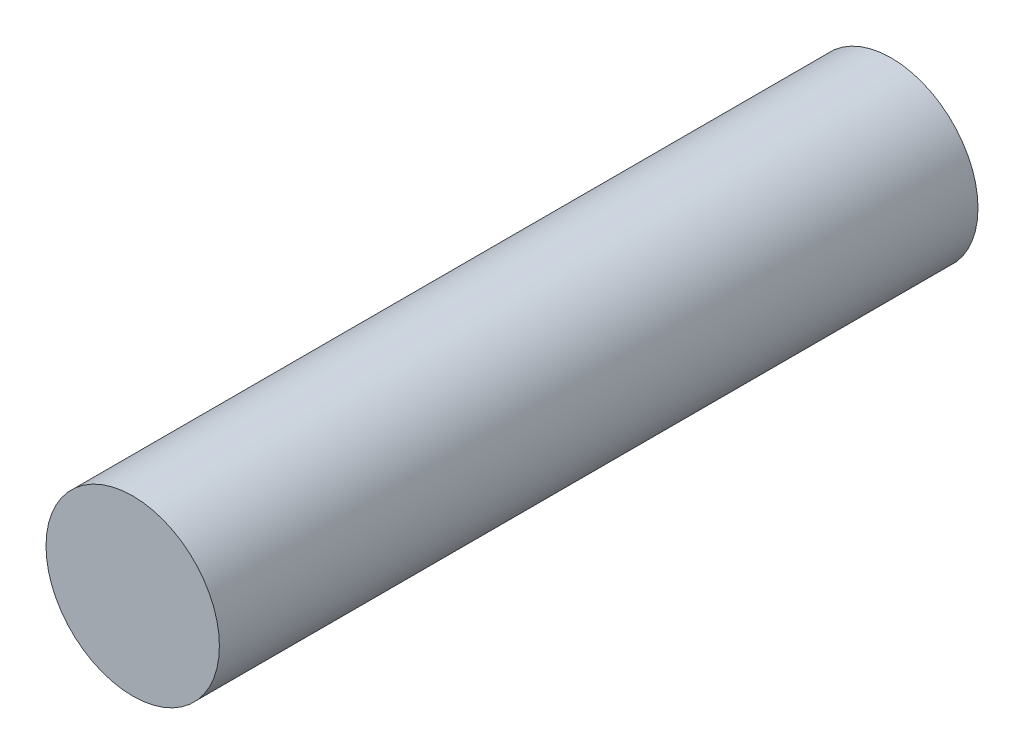
SolidWorks part; units mm, degrees
ref_plane "Front Plane" through (0, 0, 0) normal (0, 0, 1) x (1, 0, 0)
ref_plane "Top Plane" through (0, 0, 0) normal (0, 1, 0) x (1, 0, 0)
ref_plane "Right Plane" through (0, 0, 0) normal (1, 0, 0) x (0, 0, -1)
sketch "Sketch1" plane through (0, 0, 0) normal (0, 1, 0) x (1, 0, 0)
  line L1 (0, 0) -> (4, 0)
  line L2 (0, 0) -> (0, 35)
  line L3 (0, 35) -> (4, 35)
  line L4 (4, 0) -> (4, 35)
  dimension "D1" = 4
  dimension "D2" = 35
revolve "Revolve1" add sketch "Sketch1" angle 360 about L2
